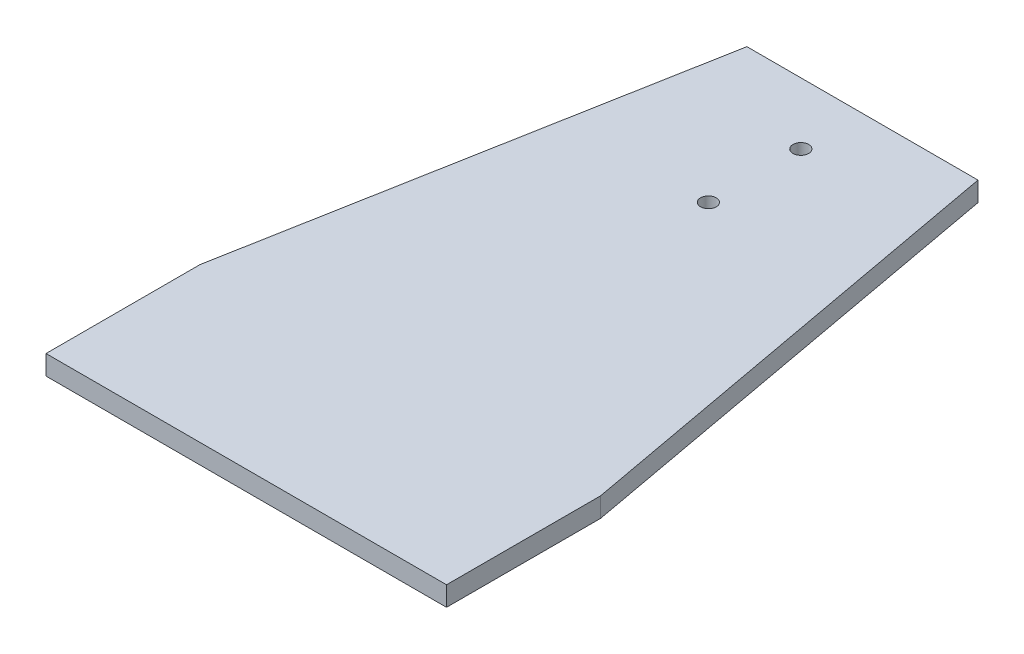
SolidWorks part; units mm, degrees
ref_plane "Front Plane" through (0, 0, 0) normal (0, 0, 1) x (1, 0, 0)
ref_plane "Top Plane" through (0, 0, 0) normal (0, 1, 0) x (1, 0, 0)
ref_plane "Right Plane" through (0, 0, 0) normal (1, 0, 0) x (0, 0, -1)
sketch "Sketch1" plane through (0, 0, 0) normal (0, 1, 0) x (1, 0, 0)
  line L0 (-37.5, 175) -> (37.5, 175)
  line L1 (-65, 25) -> (65, 25) construction
  line L2 (-65, 25) -> (-65, -25)
  line L3 (-65, -25) -> (65, -25)
  line L4 (65, 25) -> (65, -25)
  line L5 (-65, 25) -> (65, -25) construction
  line L6 (-65, -25) -> (65, 25) construction
  line L7 (-37.5, 175) -> (-65, 25)
  line L8 (37.5, 175) -> (65, 25)
  line L9 (0, 175) -> (0, 25) construction
  circle A0 centre (0, 155) radius 2.55
  circle A1 centre (0, 125) radius 2.55
  point P0 (0, 0)
  point P14 (0, 57.6751)
  point P15 (0, 44.9417)
  point P16 (0, 0)
  point P17 (0, 0)
  dimension "D1" = 5.1
  dimension "D2" = 130
  dimension "D3" = 50
  dimension "D4" = 150
  dimension "D5" = 30
  dimension "D6" = 150
  dimension "D7" = 75
extrude "Boss-Extrude1" add sketch "Sketch1" along normal blind 6.35
